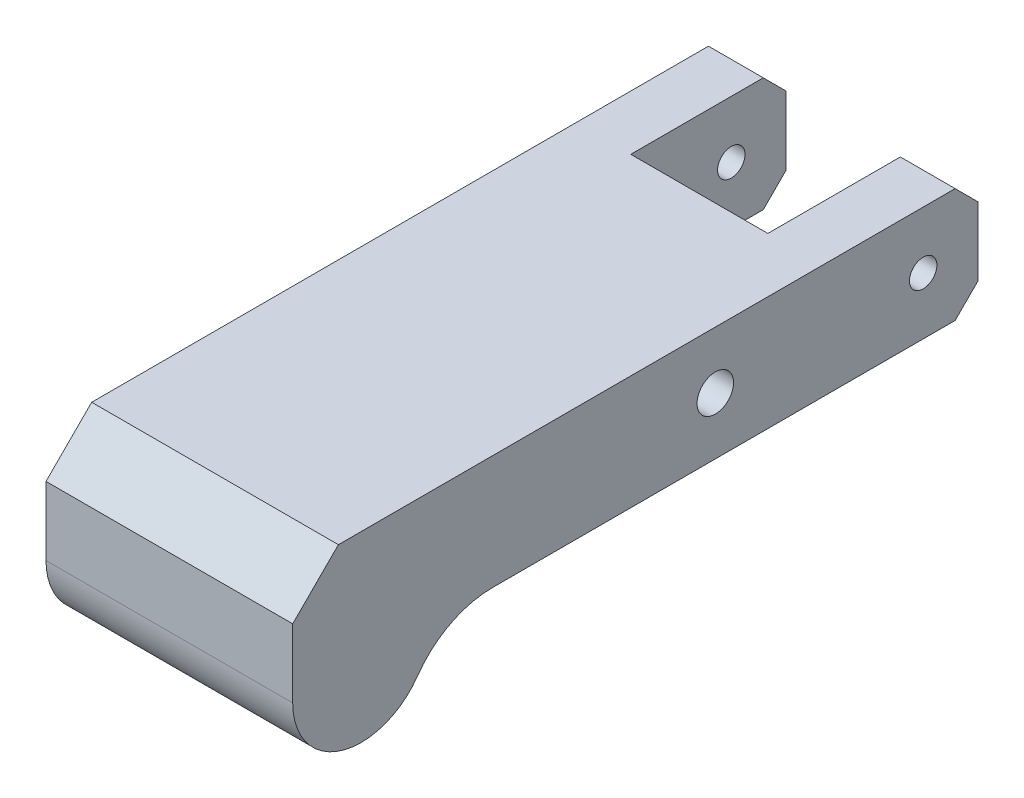
SolidWorks part; units mm, degrees
ref_plane "Ön Düzlem" through (0, 0, 0) normal (0, 0, 1) x (1, 0, 0)
ref_plane "Üst Düzlem" through (0, 0, 0) normal (0, 1, 0) x (1, 0, 0)
ref_plane "Sağ Düzlem" through (0, 0, 0) normal (1, 0, 0) x (0, 0, -1)
sketch "Çizim1" plane through (0, 0, 0) normal (1, 0, 0) x (0, 0, -1)
  line L0 (-185.4545, 5.8442) -> (-175.4545, 15.8442)
  line L1 (-175.4545, 15.8442) -> (-40.4545, 15.8442)
  line L2 (-185.4545, 5.8442) -> (-185.4545, -9.1558)
  line L3 (-141.7317, -9.1558) -> (-40.4545, -9.1558)
  line L4 (-35.4545, 10.8442) -> (-35.4545, -4.1558)
  line L5 (-40.4545, -9.1558) -> (-35.4545, -4.1558)
  line L6 (-40.4545, 15.8442) -> (-35.4545, 10.8442)
  arc A0 (-185.4545, -9.1558) -> (-158.1448, -17.7273) centre (-170.4545, -9.1558) ccw
  arc A1 (-158.1448, -17.7273) -> (-141.7317, -9.1558) centre (-141.7317, -29.1558) cw
  point P0 (-185.4545, 15.8442)
  point P1 (-35.4545, -9.1558)
  point P3 (-35.4545, 15.8442)
  dimension "D3" = 30
  dimension "D5" = 20
  dimension "D1" = 150
  dimension "D2" = 25
  dimension "D4" = 5
  dimension "D7" = 5
  dimension "D8" = 45
extrude "Yükseklik-Ekstrüzyon1" add sketch "Çizim1" along normal blind 54
sketch "Çizim2" plane through (0, 15.8442, 0) normal (0, 1, 0) x (1, 0, 0)
  line L0 (54, -35.4545) -> (0, -35.4545) construction
  line L1 (12, -35.4545) -> (42, -35.4545)
  line L2 (12, -35.4545) -> (12, -69.4545)
  line L3 (12, -69.4545) -> (42, -69.4545)
  line L4 (42, -35.4545) -> (42, -69.4545)
  line L5 (0, -40.4545) -> (0, -175.4545) construction
  line L6 (54, -40.4545) -> (54, -175.4545) construction
  dimension "D1" = 34
  dimension "D2" = 12
  dimension "D3" = 12
extrude "Kes-Ekstrüzyon1" cut sketch "Çizim2" against normal through all
sketch "Çizim3" plane through (54, 0, 0) normal (1, 0, 0) x (0, 0, -1)
  line L0 (-40.4545, 15.8442) -> (-175.4545, 15.8442) construction
  line L1 (-35.4545, -4.1558) -> (-35.4545, 10.8442) construction
  circle A0 centre (-47.4545, 3.3442) radius 3
  circle A1 centre (-92.9545, 3.3442) radius 4
  dimension "D1" = 6
  dimension "D4" = 8
  dimension "D2" = 12.5
  dimension "D3" = 12.5
  dimension "D5" = 12
  dimension "D6" = 45.5
extrude "Kes-Ekstrüzyon2" cut sketch "Çizim3" against normal through all
